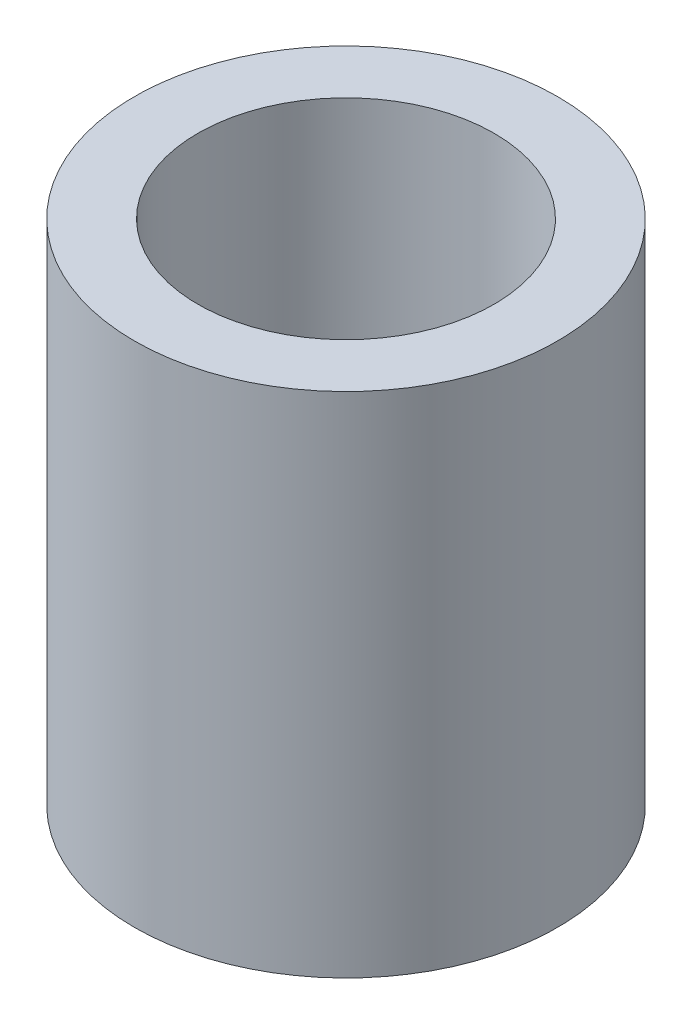
SolidWorks part; units mm, degrees
material "6061-T6 (SS)"
ref_plane "Front Plane" through (0, 0, 0) normal (0, 0, 1) x (1, 0, 0)
ref_plane "Top Plane" through (0, 0, 0) normal (0, 1, 0) x (1, 0, 0)
ref_plane "Right Plane" through (0, 0, 0) normal (1, 0, 0) x (0, 0, -1)
sketch "Sketch1" plane through (0, 0, 0) normal (0, 1, 0) x (1, 0, 0)
  circle A0 centre (0, 0) radius 7.9375
  circle A1 centre (0, 0) radius 5.5562
  dimension "D1" = 15.875
  dimension "D2" = 11.1125
extrude "Boss-Extrude1" add sketch "Sketch1" along normal blind 19.05
